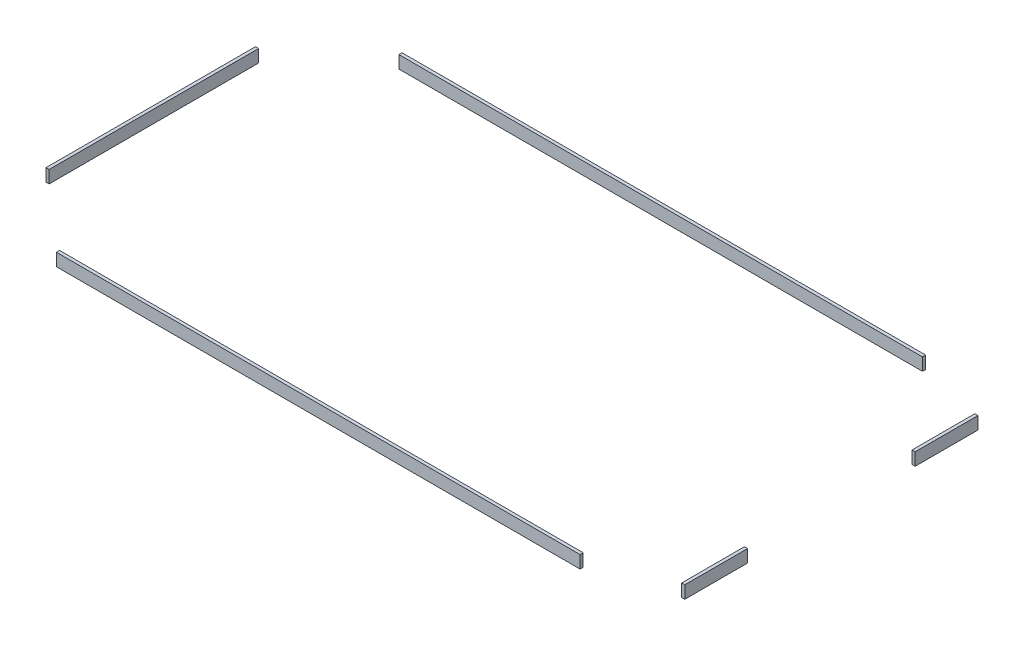
SolidWorks part; units mm, degrees
material "12Х18Н10Т ГОСТ 4543-71"
ref_plane "Спереди" through (0, 0, 0) normal (0, 0, 1) x (1, 0, 0)
ref_plane "Сверху" through (0, 0, 0) normal (0, 1, 0) x (1, 0, 0)
ref_plane "Справа" through (0, 0, 0) normal (1, 0, 0) x (0, 0, -1)
sketch "Эскиз1" plane through (0, 0, 0) normal (0, 1, 0) x (1, 0, 0)
  line L1 (161.75, -81.75) -> (-161.75, -81.75)
  line L2 (161.75, -81.75) -> (161.75, 81.75)
  line L3 (161.75, 81.75) -> (-161.75, 81.75)
  line L4 (-161.75, -81.75) -> (-161.75, 81.75)
  line L5 (0, 81.75) -> (0, -81.75) construction
  line L6 (161.75, 0) -> (-161.75, 0) construction
  point P0 (0, 0)
  dimension "D1" = 323.5
  dimension "D2" = 163.5
other "Квадрат 20 X 20(1)"
ref_plane "Плоскость1" through (161.75, 0, -81.75) normal (-1, 0, 0) x (0, 0, 1)
sketch "Sketch1" plane through (161.75, 0, -81.75) normal (-1, 0, 0) x (0, 0, 1)
  line L4 (-0.75, -3) -> (0.75, -3)
  line L5 (-0.75, -3) -> (-0.75, 3)
  line L6 (0.75, 3) -> (-0.75, 3)
  line L7 (0.75, 3) -> (0.75, -3)
  point P0 (-0.75, 0)
  point P1 (0.75, 0)
  point P2 (0, 3)
  point P3 (0, -3)
  point P4 (0, 0)
  point P5 (-0.75, -3)
  point P6 (0.75, -3)
  point P7 (0.75, 3)
  point P8 (-0.75, 3)
  point P10 (0.75, 0)
  point P12 (-0.75, 0)
  point P13 (0, -3)
  point P14 (0, 0)
  dimension "D1" = 1.5
  dimension "V_leg" = 6
sketch "Эскиз3" plane through (0, 0, 0) normal (0, 1, 0) x (1, 0, 0)
  line L0 (0, 120.2562) -> (0, -120.2562) construction
  line L1 (-165, 90) -> (-125, 90)
  line L2 (-165, 90) -> (-165, 50)
  line L3 (-165, 50) -> (-125, 50)
  line L4 (-125, 90) -> (-125, 50)
  line L5 (-145, 50) -> (-145, 90) construction
  line L6 (-165, 70) -> (-125, 70) construction
  line L7 (-173.2351, 0) -> (173.2351, 0) construction
  line L16 (-165, -90) -> (-165, -50)
  line L17 (-165, -90) -> (-125, -90)
  line L18 (-125, -90) -> (-125, -50)
  line L19 (-165, -50) -> (-125, -50)
  line L22 (217.5436, -100.4938) -> (217.5436, -70)
  line L23 (127.1757, -40) -> (173.2351, -40)
  line L24 (127.1757, -40) -> (127.1757, 40)
  line L25 (127.1757, 40) -> (173.2351, 40)
  line L26 (173.2351, -40) -> (173.2351, 40)
  line L27 (150.2054, 40) -> (150.2054, -40) construction
  line L28 (127.1757, 0) -> (173.2351, 0) construction
  line L29 (217.5436, 100.4938) -> (125, 100.4938)
  line L30 (217.5436, 100.4938) -> (217.5436, 70)
  line L31 (217.5436, 70) -> (125, 70)
  line L32 (125, 100.4938) -> (125, 70)
  line L33 (171.2718, 70) -> (171.2718, 100.4938) construction
  line L34 (217.5436, 85.2469) -> (125, 85.2469) construction
  line L35 (217.5436, -70) -> (125, -70)
  line L36 (125, -100.4938) -> (125, -70)
  line L37 (217.5436, -100.4938) -> (125, -100.4938)
  point P0 (-145, 70)
  point P8 (171.2718, 85.2469)
  point P10 (150.2054, 0)
  dimension "D1" = 40
  dimension "D2" = 40
  dimension "D3" = 100
  dimension "D4" = 250
  dimension "D5" = 80
  dimension "D6" = 125
  dimension "D7" = 30
extrude "Вырез-Вытянуть1" cut sketch "Эскиз3" against normal through all and the other way through all
equation "\"D2@Эскиз3\"=\"D1@Эскиз3\""
equation "\"D6@Эскиз3\"=\"D4@Эскиз3\"/2"
